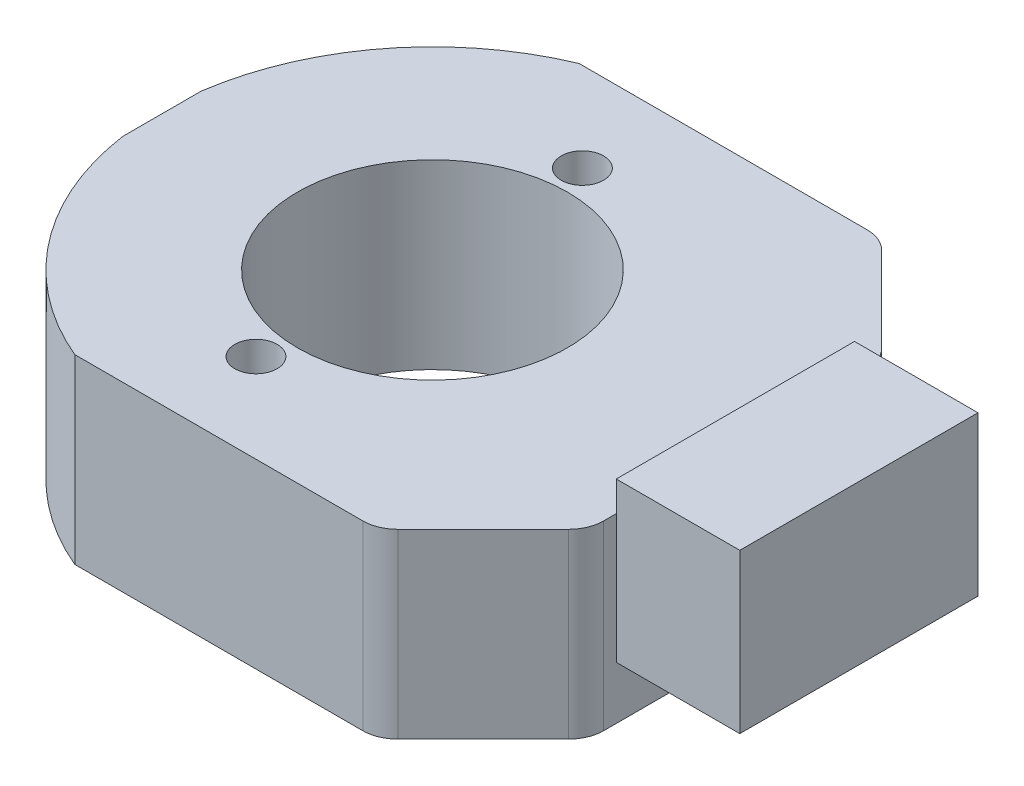
SolidWorks part; units mm, degrees
ref_plane "正面" through (0, 0, 0) normal (0, 0, 1) x (1, 0, 0)
ref_plane "平面" through (0, 0, 0) normal (0, 1, 0) x (1, 0, 0)
ref_plane "右側面" through (0, 0, 0) normal (1, 0, 0) x (0, 0, -1)
sketch "ｽｹｯﾁ1" plane through (0, 0, 0) normal (0, 1, 0) x (1, 0, 0)
  line L1 (-15.33, 14.29) -> (17.17, 14.29)
  line L2 (-15.33, 14.29) -> (-15.33, -14.29)
  line L3 (-15.33, -14.29) -> (17.17, -14.29)
  line L4 (17.17, 14.29) -> (17.17, -14.29)
  circle A0 centre (0, 0) radius 7.65
  arc A2 (-5.978, 14.29) -> (-15.33, 2.2206) centre (0, 0) ccw
  arc A3 (-15.33, -2.2206) -> (-5.978, -14.29) centre (0, 0) ccw
  point P7 (-15.33, 0)
  dimension "D1" = 15.3
  dimension "D5" = 30.98
  dimension "D2" = 28.58
  dimension "D3" = 32.5
  dimension "D4" = 15.33
extrude "ﾎﾞｽ - 押し出し1" add sketch "ｽｹｯﾁ1" along normal blind 10.3
sketch "ｽｹｯﾁ2" plane through (0, 0, 0) normal (0, -1, 0) x (1, 0, 0)
  line L0 (-0.75, -14.29) -> (-0.75, 14.29) construction
  line L1 (-5.978, -14.29) -> (17.17, -14.29) construction
  line L2 (-5.978, 14.29) -> (17.17, 14.29) construction
  line L3 (0, 0) -> (17.17, 0) construction
  line L4 (17.17, -14.29) -> (17.17, 14.29) construction
  circle A0 centre (-0.75, 9.25) radius 1.2
  circle A1 centre (-0.75, -9.25) radius 1.2
  dimension "D1" = 2.4
  dimension "D2" = 9.25
  dimension "D3" = 0.75
extrude "ｶｯﾄ - 押し出し1" cut sketch "ｽｹｯﾁ2" against normal blind 10.5
chamfer "面取り1" distance 6 angle 45
fillet "ﾌｨﾚｯﾄ1" radius 2
sketch "ｽｹｯﾁ4" plane through (0, 0, 0) normal (0, 1, 0) x (1, 0, 0)
  line L0 (17.17, 14.29) -> (17.17, -14.29) construction
  line L1 (17.17, 6.75) -> (24.17, 6.75)
  line L2 (17.17, 6.75) -> (17.17, -6.75)
  line L3 (17.17, -6.75) -> (24.17, -6.75)
  line L4 (24.17, 6.75) -> (24.17, -6.75)
  point P6 (24.17, 0)
  dimension "D1" = 13.5
  dimension "D2" = 7
extrude "ﾎﾞｽ - 押し出し2" add sketch "ｽｹｯﾁ4" along normal blind 9 from offset 3
